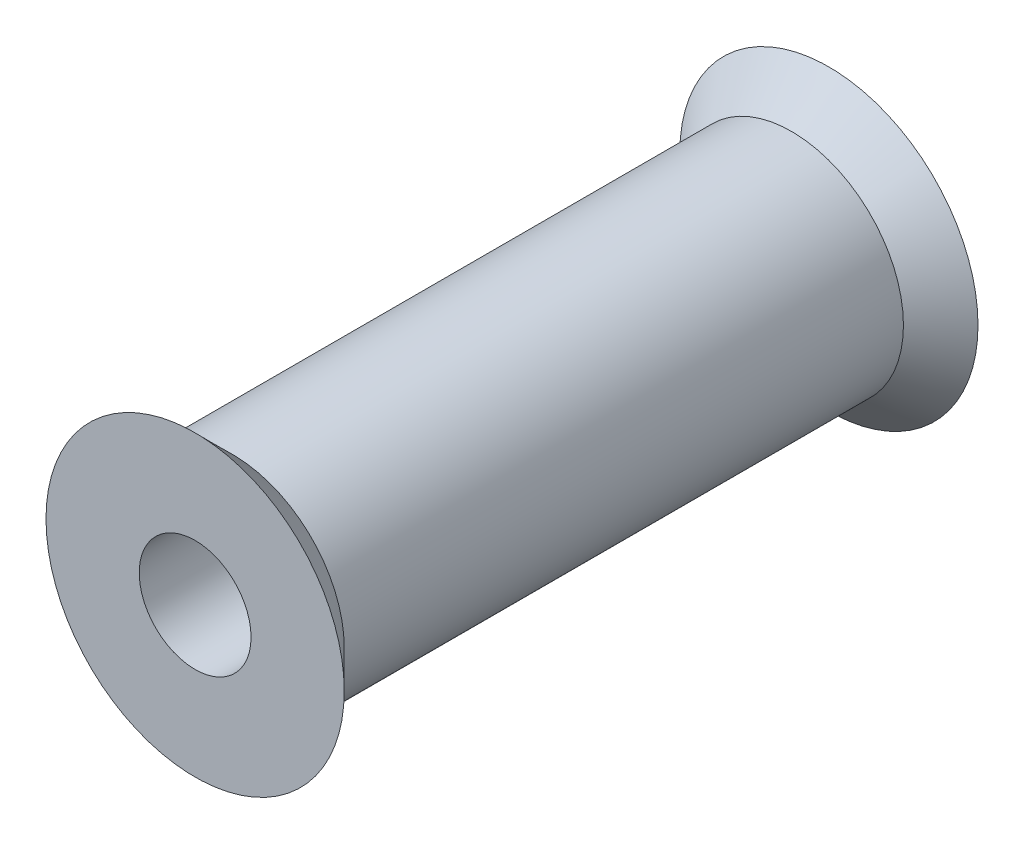
SolidWorks part; units mm, degrees
ref_plane "前视基准面" through (0, 0, 0) normal (0, 0, 1) x (1, 0, 0)
ref_plane "上视基准面" through (0, 0, 0) normal (0, 1, 0) x (1, 0, 0)
ref_plane "右视基准面" through (0, 0, 0) normal (1, 0, 0) x (0, 0, -1)
other "Configuration Table"
sketch "草图2" plane through (0, 0, 0) normal (0, 1, 0) x (1, 0, 0)
  line L0 (0, 0) -> (8, 0)
  line L1 (4, 0) -> (4, 17)
  line L2 (5.5, 0) -> (5.5, 17)
  line L3 (2.5, 0) -> (2.5, 17)
  line L4 (1, 0) -> (1, 17)
  line L5 (7, 0) -> (7, 17)
  line L6 (8, 17) -> (0, 17)
  line L7 (0, 0) -> (1, 1)
  line L8 (8, 0) -> (7, 1)
  line L9 (0, 17) -> (1, 16)
  line L10 (8, 17) -> (7, 16)
  point P16 (8, 17)
  point P19 (0, 17)
  dimension "D1" = 1.5
  dimension "D2" = 1.5
  dimension "D3" = 3
  dimension "D4" = 3
  dimension "D5" = 3
  dimension "D6" = 3
  dimension "D7" = 17
  dimension "D8" = 1.5
  dimension "D9" = 1.5
  dimension "D10" = 135
  dimension "D11" = 135
  dimension "D12" = 45
  dimension "D13" = 135
  dimension "D14" = 1
  dimension "D15" = 1
  dimension "D16" = 1
  dimension "D17" = 1
revolve "旋转1" add sketch "草图2" angle 360 about L1
